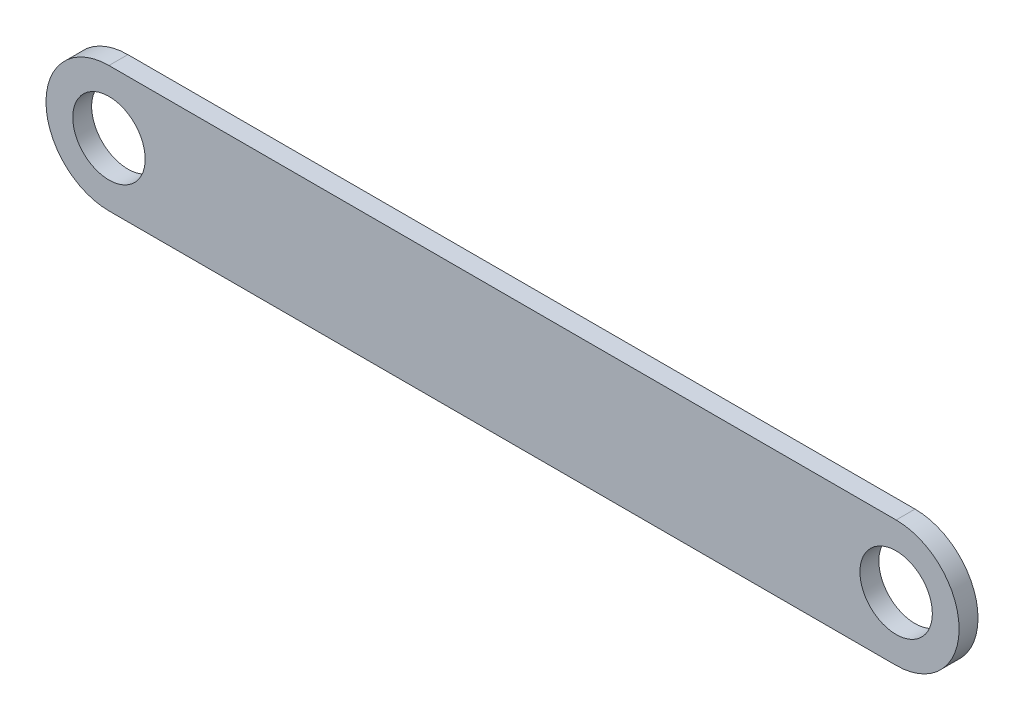
SolidWorks part; units mm, degrees
ref_plane "Front Plane" through (0, 0, 0) normal (0, 0, 1) x (1, 0, 0)
ref_plane "Top Plane" through (0, 0, 0) normal (0, 1, 0) x (1, 0, 0)
ref_plane "Right Plane" through (0, 0, 0) normal (1, 0, 0) x (0, 0, -1)
sketch "Sketch1" plane through (0, 0, 0) normal (0, 0, 1) x (1, 0, 0)
  line L0 (-62.5, 0) -> (62.5, 0) construction
  line L1 (-62.5, 10) -> (62.5, 10)
  line L2 (-62.5, -10) -> (62.5, -10)
  arc A0 (-62.5, 10) -> (-62.5, -10) centre (-62.5, 0) ccw
  arc A1 (62.5, -10) -> (62.5, 10) centre (62.5, 0) ccw
  circle A2 centre (-62.5, 0) radius 5.75
  circle A3 centre (62.5, 0) radius 5.75
  point P2 (0, 0)
  dimension "D2" = 11.5
  dimension "D3" = 10
  dimension "D1" = 125
extrude "Boss-Extrude1" add sketch "Sketch1" along normal blind 3
